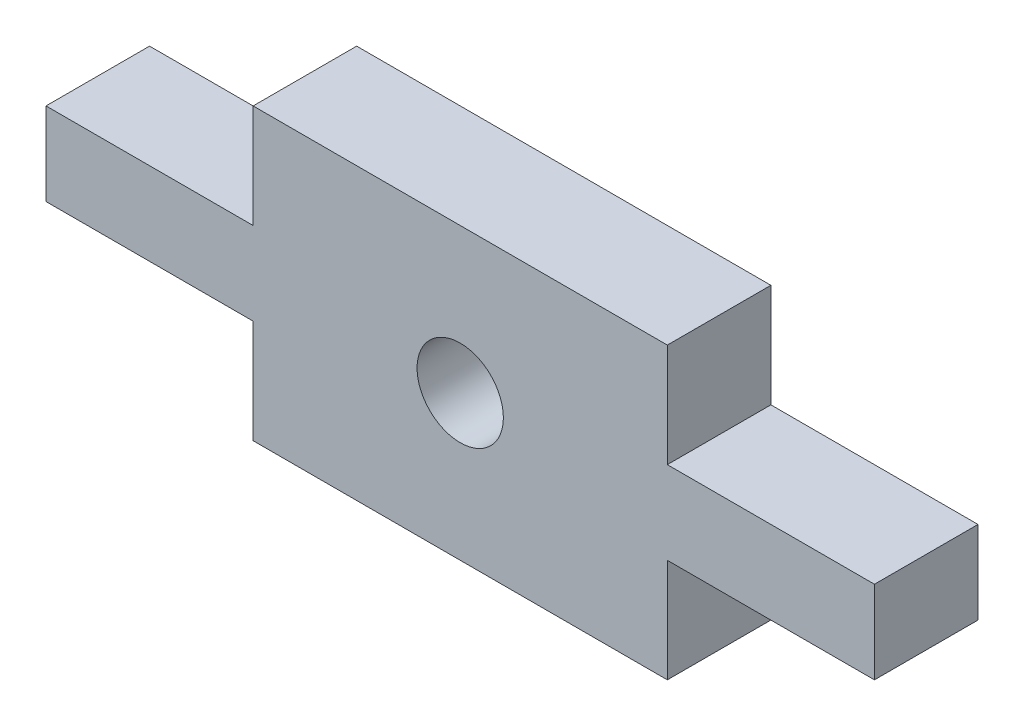
SolidWorks part; units mm, degrees
ref_plane "前基準面" through (0, 0, 0) normal (0, 0, 1) x (1, 0, 0)
ref_plane "上基準面" through (0, 0, 0) normal (0, 1, 0) x (1, 0, 0)
ref_plane "右基準面" through (0, 0, 0) normal (1, 0, 0) x (0, 0, -1)
sketch "草圖1" plane through (0, 0, 0) normal (0, 0, 1) x (1, 0, 0)
  line L0 (218.7995, 139.9841) -> (218.7994, 136.984) construction
  line L1 (224.7994, 139.9839) -> (218.7995, 139.9841) construction
  line L2 (218.7994, 142.3839) -> (224.7994, 142.3839) construction
  line L3 (218.7995, 145.384) -> (218.7994, 142.3839) construction
  line L4 (206.7996, 145.3842) -> (218.7995, 145.384) construction
  line L5 (206.7994, 142.3841) -> (206.7996, 145.3842) construction
  line L6 (206.7994, 136.9841) -> (206.7994, 139.9842) construction
  line L7 (200.7994, 139.9842) -> (200.7994, 142.3842) construction
  line L8 (206.7994, 139.9842) -> (200.7994, 139.9842) construction
  line L9 (200.7994, 142.3842) -> (206.7994, 142.3841) construction
  line L10 (218.7995, 139.9841) -> (218.7994, 136.984)
  line L11 (224.7994, 139.9839) -> (218.7995, 139.9841)
  line L12 (218.7994, 142.3839) -> (224.7994, 142.3839)
  line L13 (218.7995, 145.384) -> (218.7994, 142.3839)
  line L14 (206.7996, 145.3842) -> (218.7995, 145.384)
  line L15 (206.7994, 142.3841) -> (206.7996, 145.3842)
  line L16 (206.7994, 136.9841) -> (206.7994, 139.9842)
  line L17 (200.7994, 139.9842) -> (200.7994, 142.3842)
  line L18 (206.7994, 139.9842) -> (200.7994, 139.9842)
  line L19 (200.7994, 142.3842) -> (206.7994, 142.3841)
  line L20 (224.7994, 142.3839) -> (224.7994, 139.9839)
  line L21 (206.7994, 136.9841) -> (218.7994, 136.984)
  circle A0 centre (212.7995, 141.1841) radius 1.25 construction
  circle A1 centre (212.7995, 141.1841) radius 1.25
extrude "填料-伸長1" add sketch "草圖1" along normal blind 3
